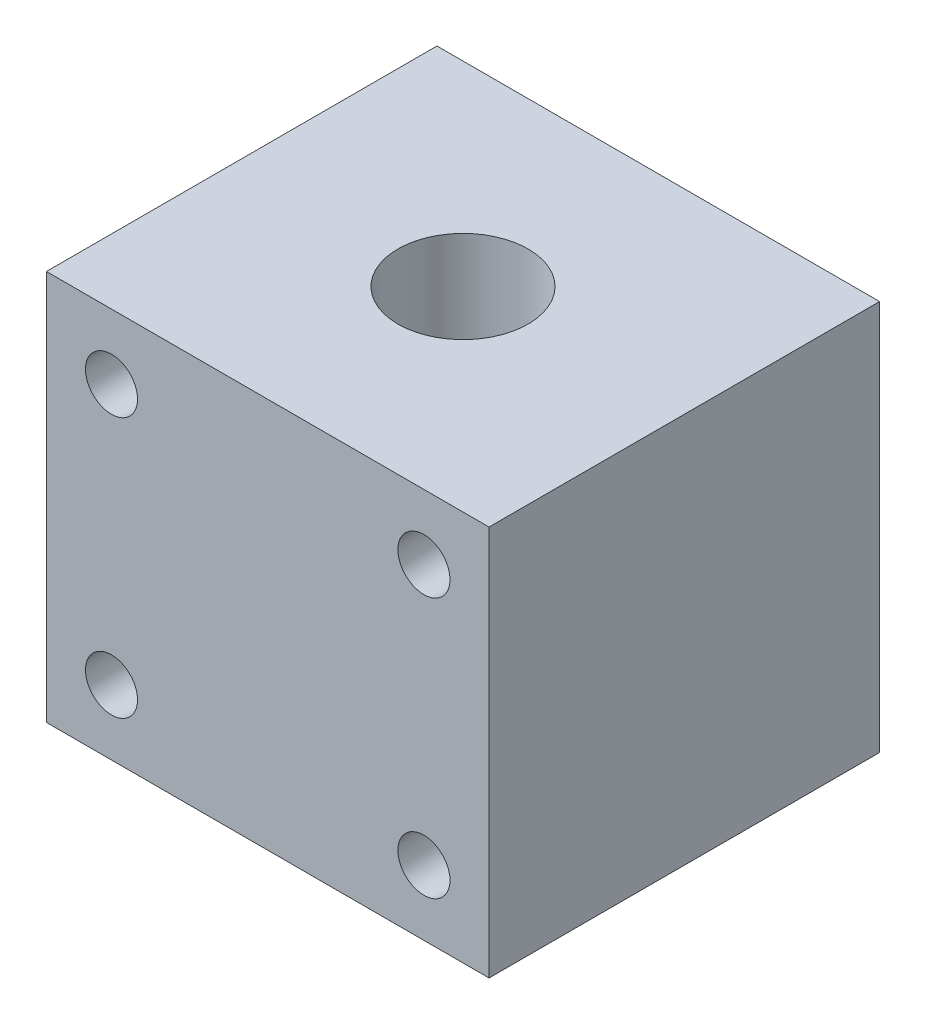
SolidWorks part; units mm, degrees
ref_plane "Front Plane" through (0, 0, 0) normal (0, 0, 1) x (1, 0, 0)
ref_plane "Top Plane" through (0, 0, 0) normal (0, 1, 0) x (1, 0, 0)
ref_plane "Right Plane" through (0, 0, 0) normal (1, 0, 0) x (0, 0, -1)
sketch "Sketch1" plane through (0, 0, 0) normal (0, 1, 0) x (1, 0, 0)
  line L0 (0, -15) -> (34, -15) construction
  line L1 (0, 0) -> (34, 0)
  line L2 (0, 0) -> (0, -30)
  line L3 (0, -30) -> (34, -30)
  line L4 (34, 0) -> (34, -30)
  line L5 (17, 0) -> (17, -30) construction
  circle A0 centre (17, -15) radius 5
  dimension "D3" = 10
  dimension "D1" = 34
  dimension "D2" = 30
extrude "Boss-Extrude1" add sketch "Sketch1" along normal blind 30
sketch "Sketch2" plane through (0, 0, 0) normal (0, 0, -1) x (-1, 0, 0)
  line L0 (-17, 30) -> (-17, 0) construction
  line L1 (-34, 30) -> (0, 30) construction
  line L2 (-34, 0) -> (0, 0) construction
  line L3 (-34, 15) -> (0, 15) construction
  line L4 (-34, 30) -> (-34, 0) construction
  line L5 (0, 30) -> (0, 0) construction
  circle A0 centre (-29, 25) radius 2
  circle A1 centre (-5, 25) radius 2
  circle A2 centre (-5, 5) radius 2
  circle A3 centre (-29, 5) radius 2
  dimension "D3" = 4
  dimension "D1" = 5
  dimension "D2" = 5
extrude "Cut-Extrude1" cut sketch "Sketch2" against normal through all both and the other way through all
